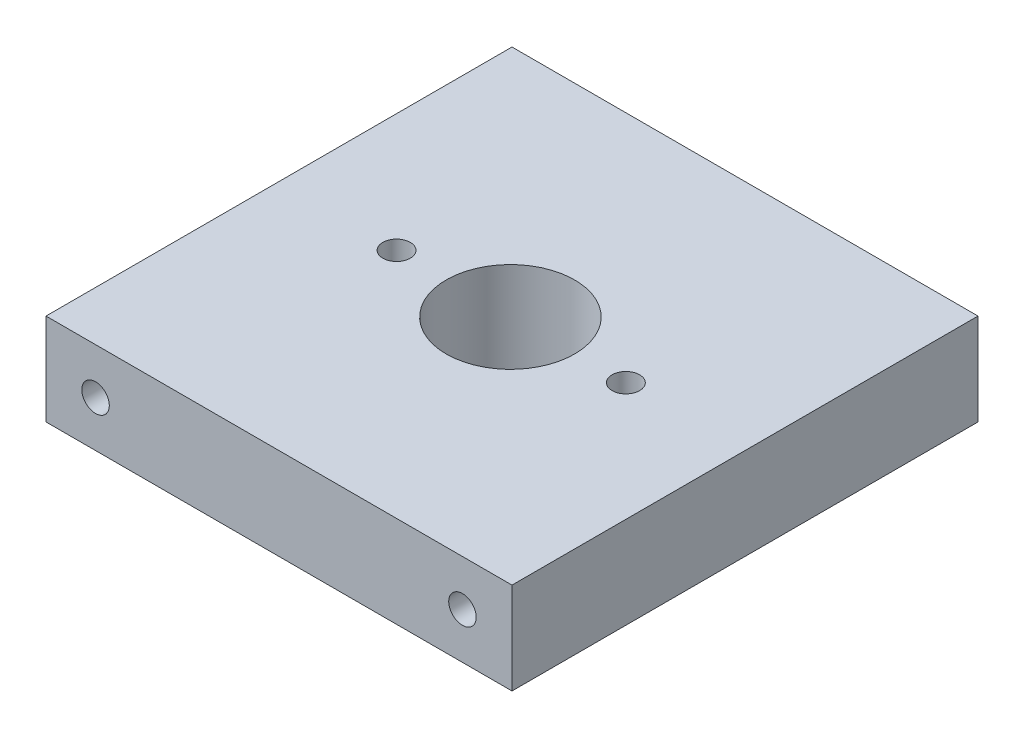
SolidWorks part; units mm, degrees
ref_plane "Front Plane" through (0, 0, 0) normal (0, 0, 1) x (1, 0, 0)
ref_plane "Top Plane" through (0, 0, 0) normal (0, 1, 0) x (1, 0, 0)
ref_plane "Right Plane" through (0, 0, 0) normal (1, 0, 0) x (0, 0, -1)
sketch "Sketch1" plane through (0, 0, 0) normal (0, 1, 0) x (1, 0, 0)
  line L1 (-25.4, 25.4) -> (25.4, 25.4)
  line L2 (-25.4, 25.4) -> (-25.4, -25.4)
  line L3 (-25.4, -25.4) -> (25.4, -25.4)
  line L4 (25.4, 25.4) -> (25.4, -25.4)
  line L5 (-25.4, 25.4) -> (25.4, -25.4) construction
  line L6 (-25.4, -25.4) -> (25.4, 25.4) construction
  point P0 (0, 0)
  dimension "D1" = 50.8
  dimension "D2" = 50.8
extrude "Boss-Extrude1" add sketch "Sketch1" along normal blind 10
sketch "Sketch2" plane through (0, 10, 0) normal (0, 1, 0) x (1, 0, 0)
  line L0 (-25.4, 0) -> (25.4, -0.3444) construction
  line L1 (-25.4, 25.4) -> (-25.4, -25.4) construction
  line L2 (25.4, -25.4) -> (25.4, 25.4) construction
  line L3 (0, 25.4) -> (0, -25.4) construction
  line L4 (25.4, 25.4) -> (-25.4, 25.4) construction
  line L5 (-25.4, -25.4) -> (25.4, -25.4) construction
  circle A0 centre (0, -0.1722) radius 7
  circle A1 centre (-12.5, -0.0875) radius 1.5
  circle A2 centre (12.5, -0.0875) radius 1.5
  dimension "D1" = 14
  dimension "D2" = 3
  dimension "D3" = 25
extrude "Cut-Extrude1" cut sketch "Sketch2" against normal through all
sketch "Sketch3" plane through (0, 0, -25.4) normal (0, 0, -1) x (-1, 0, 0)
  line L0 (25.4, 5) -> (-25.4, 5) construction
  line L1 (25.4, 10) -> (25.4, 0) construction
  line L2 (-25.4, 10) -> (-25.4, 0) construction
  line L3 (0, 0) -> (0, 10) construction
  line L4 (-25.4, 0) -> (25.4, 0) construction
  line L5 (-25.4, 10) -> (25.4, 10) construction
  circle A0 centre (20, 5) radius 1.5
  circle A1 centre (-20, 5) radius 1.5
  dimension "D1" = 3
  dimension "D2" = 40
extrude "Cut-Extrude2" cut sketch "Sketch3" against normal through all
